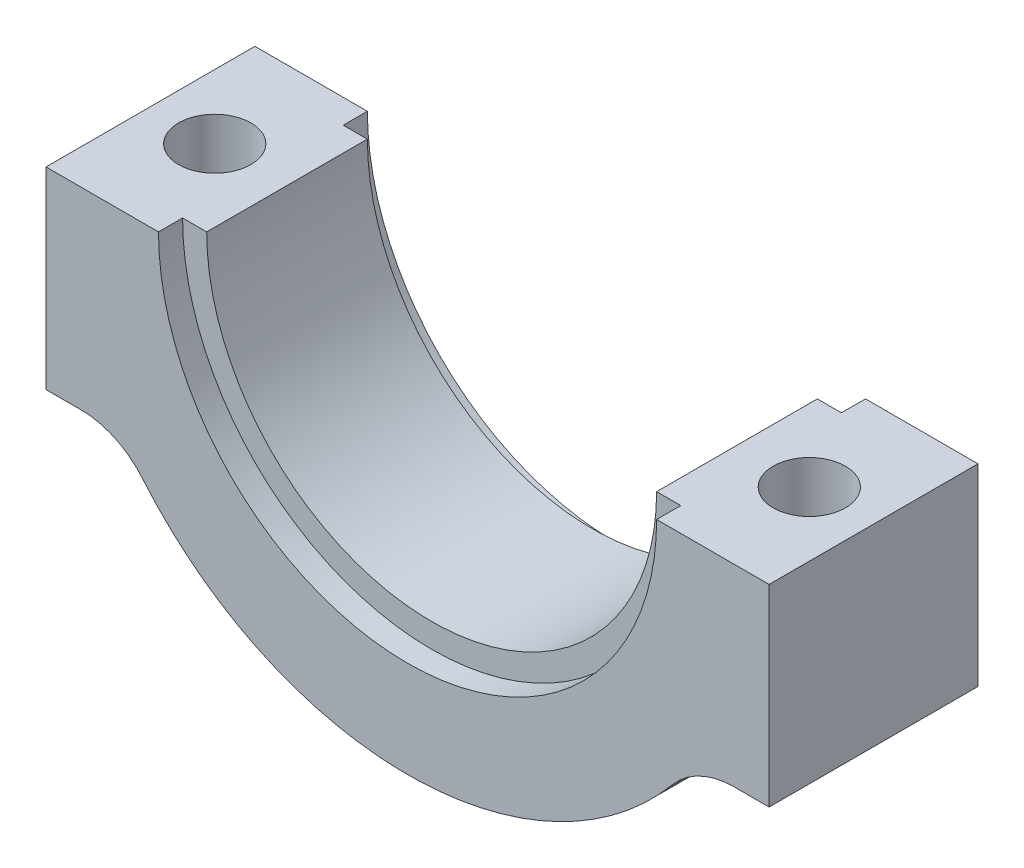
SolidWorks part; units mm, degrees
ref_plane "Спереди" through (0, 0, 0) normal (0, 0, 1) x (1, 0, 0)
ref_plane "Сверху" through (0, 0, 0) normal (0, 1, 0) x (1, 0, 0)
ref_plane "Справа" through (0, 0, 0) normal (1, 0, 0) x (0, 0, -1)
sketch "Эскиз1" plane through (0, 0, 0) normal (0, 0, 1) x (1, 0, 0)
  line L0 (0, 593.8304) -> (0, -720.0194) construction
  line L1 (920.7363, 0) -> (-1046.3271, 0) construction
  line L2 (-31, 0) -> (-45, 0)
  line L3 (-45, 0) -> (-45, -24)
  line L4 (-45, -24) -> (-40.6571, -24)
  line L5 (45, -24) -> (40.6571, -24)
  line L6 (45, 0) -> (45, -24)
  line L7 (31, 0) -> (45, 0)
  arc A0 (-40.6571, -24) -> (-32.986, -27.5849) centre (-40.6571, -34) cw
  arc A1 (-32.986, -27.5849) -> (32.986, -27.5849) centre (0, 0) ccw
  arc A2 (-31, 0) -> (31, 0) centre (0, 0) ccw
  arc A4 (40.6571, -24) -> (32.986, -27.5849) centre (40.6571, -34) ccw
  dimension "D1" = 31
  dimension "D3" = 43
  dimension "D6" = 10
  dimension "D4" = 24
  dimension "D5" = 90
extrude "Бобышка-Вытянуть1" add sketch "Эскиз1" along normal mid plane 26 contours A4 L5 L6 L7 A2 L2 L3 L4 A0 A1
sketch "Эскиз3" plane through (0, 0, 0) normal (0, 0, 1) x (1, 0, 0)
  line L0 (0, 99.3189) -> (0, -470.2464) construction
  line L1 (-468.1931, 0) -> (469.2382, 0) construction
  line L2 (-31, 0) -> (-28, 0)
  line L3 (31, 0) -> (28, 0)
  arc A0 (-28, 0) -> (28, 0) centre (0, 0) ccw
  arc A1 (-31, 0) -> (31, 0) centre (0, 0) ccw
  dimension "D1" = 28
extrude "Бобышка-Вытянуть2" add sketch "Эскиз3" along normal mid plane 20
sketch "Эскиз4" plane through (0, 0, 0) normal (0, 1, 0) x (1, 0, 0)
  line L0 (699.4318, 0) -> (-699.4318, 0) construction
  line L1 (0, 336.981) -> (0, -370.1162) construction
  circle A0 centre (-37, 0) radius 4.5
  circle A1 centre (37, 0) radius 4.5
  point P4 (0, 0)
  dimension "D2" = 9
  dimension "D1" = 74
extrude "Вырез-Вытянуть1" cut sketch "Эскиз4" against normal blind 19
sketch "Эскиз5" plane through (0, -19, 0) normal (0, 1, 0) x (1, 0, 0)
  line L0 (0, 359.2257) -> (0, -370.568) construction
  circle A0 centre (-37, 0) radius 7
  circle A1 centre (37, 0) radius 7
  dimension "D1" = 14
extrude "Вырез-Вытянуть2" cut sketch "Эскиз5" against normal through all
